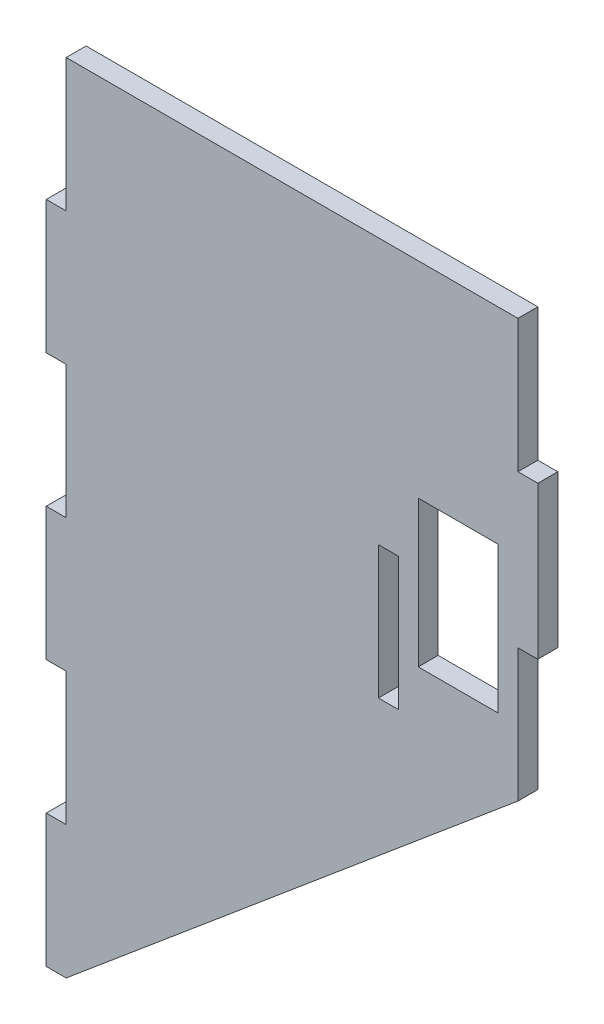
SolidWorks part; units mm, degrees
material "Acrilico TEC"
ref_plane "Front Plane" through (0, 0, 0) normal (0, 0, 1) x (1, 0, 0)
ref_plane "Top Plane" through (0, 0, 0) normal (0, 1, 0) x (1, 0, 0)
ref_plane "Right Plane" through (0, 0, 0) normal (1, 0, 0) x (0, 0, -1)
sketch "Sketch1" plane through (0, 0, 0) normal (0, 0, 1) x (1, 0, 0)
  line L0 (-3, 60) -> (-3, 40)
  line L1 (-3, 40) -> (0, 40)
  line L2 (0, 40) -> (0, 20)
  line L3 (0, 20) -> (-3, 20)
  line L4 (-3, 20) -> (-3, 0)
  line L5 (-3, 60) -> (0, 60)
  line L6 (0, 60) -> (0, 80)
  line L7 (0, 80) -> (-3, 80)
  line L8 (-3, 80) -> (-3, 100)
  line L9 (0, 120) -> (23.5, 120)
  line L10 (23.5, 120) -> (23.5, 105) construction
  line L11 (-3, 0) -> (0, 0)
  line L12 (23.5, 120) -> (68, 120)
  line L13 (68, 57.0588) -> (68, 77.0588)
  line L14 (47, 80) -> (50, 80)
  line L15 (47, 60) -> (47, 80)
  line L16 (50, 60) -> (47, 60)
  line L17 (68, 77.0588) -> (71, 77.0588)
  line L18 (71, 77.0588) -> (71, 100)
  line L19 (71, 100) -> (68, 100)
  line L20 (68, 100) -> (68, 120)
  line L21 (53, 89.0588) -> (65, 89.0588)
  line L22 (0, 0) -> (68, 57.0588)
  line L23 (0, 0) -> (3.8747, 0) construction
  line L24 (53, 89.0588) -> (53, 67.0588)
  line L25 (50, 60) -> (50, 80)
  line L26 (53, 67.0588) -> (65, 67.0588)
  line L27 (-3, 100) -> (0, 100)
  line L28 (0, 100) -> (0, 120)
  line L30 (65, 89.0588) -> (65, 67.0588)
  dimension "D2" = 12
  dimension "D3" = 20
  dimension "D4" = 23.5
  dimension "D5" = 20
  dimension "D6" = 3
  dimension "D7" = 3
  dimension "D8" = 23.5
  dimension "D9" = 15
  dimension "D10" = 20
  dimension "D11" = 20
  dimension "D13" = 40
  dimension "D14" = 20
  dimension "D15" = 3
  dimension "D16" = 22
  dimension "D17" = 3
  dimension "D18" = 10
  dimension "D19" = 3
extrude "Boss-Extrude1" add sketch "Sketch1" along normal blind 3
